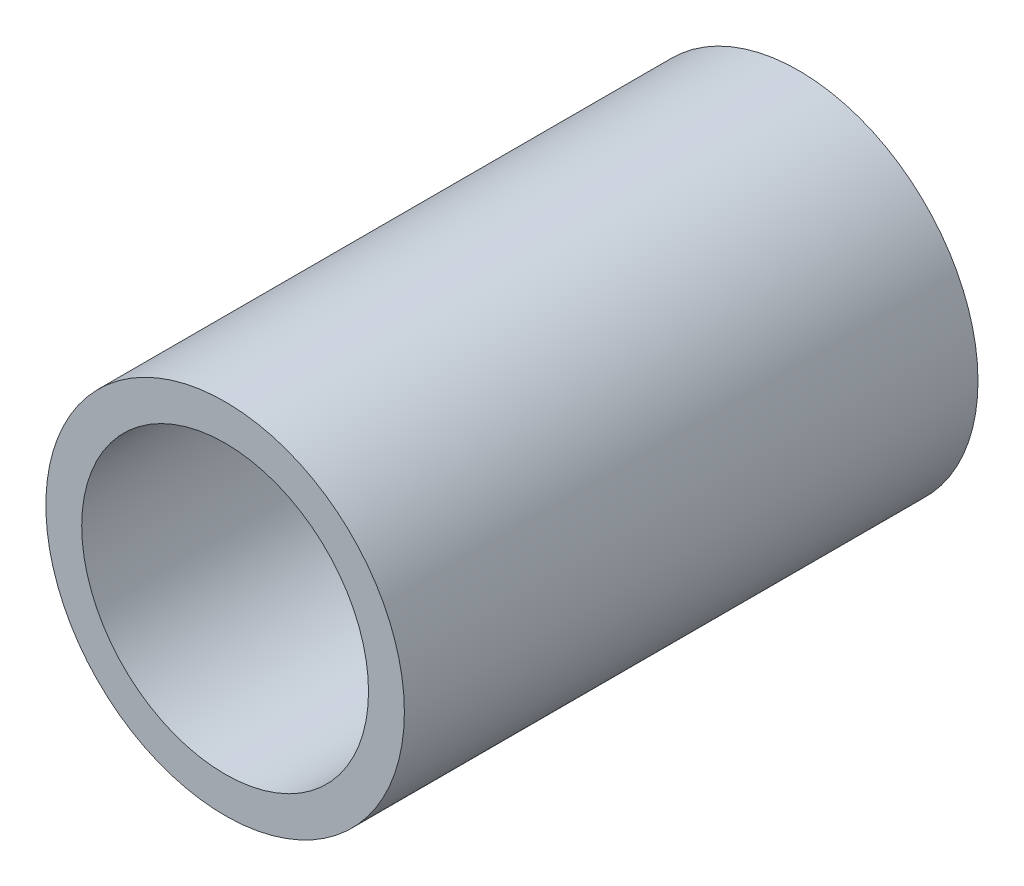
SolidWorks part; units mm, degrees
ref_plane "Front Plane" through (0, 0, 0) normal (0, 0, 1) x (1, 0, 0)
ref_plane "Top Plane" through (0, 0, 0) normal (0, 1, 0) x (1, 0, 0)
ref_plane "Right Plane" through (0, 0, 0) normal (1, 0, 0) x (0, 0, -1)
sketch "Sketch2" plane through (0, 0, 0) normal (0, 0, 1) x (1, 0, 0)
  circle A0 centre (0, 0) radius 1.9844
  dimension "D1" = 3.9688
extrude "Boss-Extrude3" add sketch "Sketch2" along normal blind 6.35 contours A0
sketch "Sketch3" plane through (0, 0, 6.35) normal (0, 0, 1) x (1, 0, 0)
  circle A0 centre (0, 0) radius 1.5875
  dimension "D1" = 3.175
extrude "Cut-Extrude1" cut sketch "Sketch3" against normal through all
